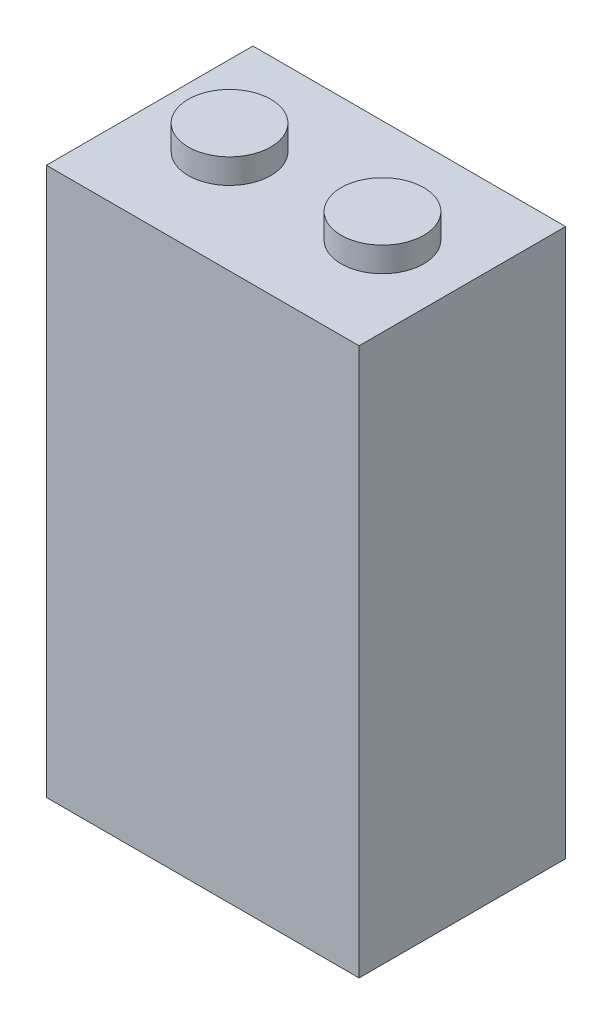
SolidWorks part; units mm, degrees
ref_plane "Front" through (0, 0, 0) normal (0, 0, 1) x (1, 0, 0)
ref_plane "Top" through (0, 0, 0) normal (0, 1, 0) x (1, 0, 0)
ref_plane "Right" through (0, 0, 0) normal (1, 0, 0) x (0, 0, -1)
sketch "Sketch1" plane through (0, 0, 0) normal (0, 1, 0) x (1, 0, 0)
  line L1 (-13.25, -8.75) -> (13.25, -8.75)
  line L2 (-13.25, -8.75) -> (-13.25, 8.75)
  line L3 (-13.25, 8.75) -> (13.25, 8.75)
  line L4 (13.25, -8.75) -> (13.25, 8.75)
  line L5 (-13.25, -8.75) -> (13.25, 8.75) construction
  line L6 (-13.25, 8.75) -> (13.25, -8.75) construction
  point P0 (0, 0)
  dimension "D1" = 17.5
  dimension "D2" = 26.5
extrude "Boss-Extrude1" add sketch "Sketch1" along normal blind 46.4
sketch "Sketch2" plane through (0, 46.4, 0) normal (0, 1, 0) x (1, 0, 0)
  line L0 (-6.48, 0) -> (6.48, 0) construction
  circle A0 centre (-6.48, 0) radius 3.5
  circle A1 centre (6.48, 0) radius 3.5
  point P4 (0, 0)
  dimension "D1" = 7
  dimension "D2" = 12.96
extrude "Boss-Extrude2" add sketch "Sketch2" along normal blind 2.1
